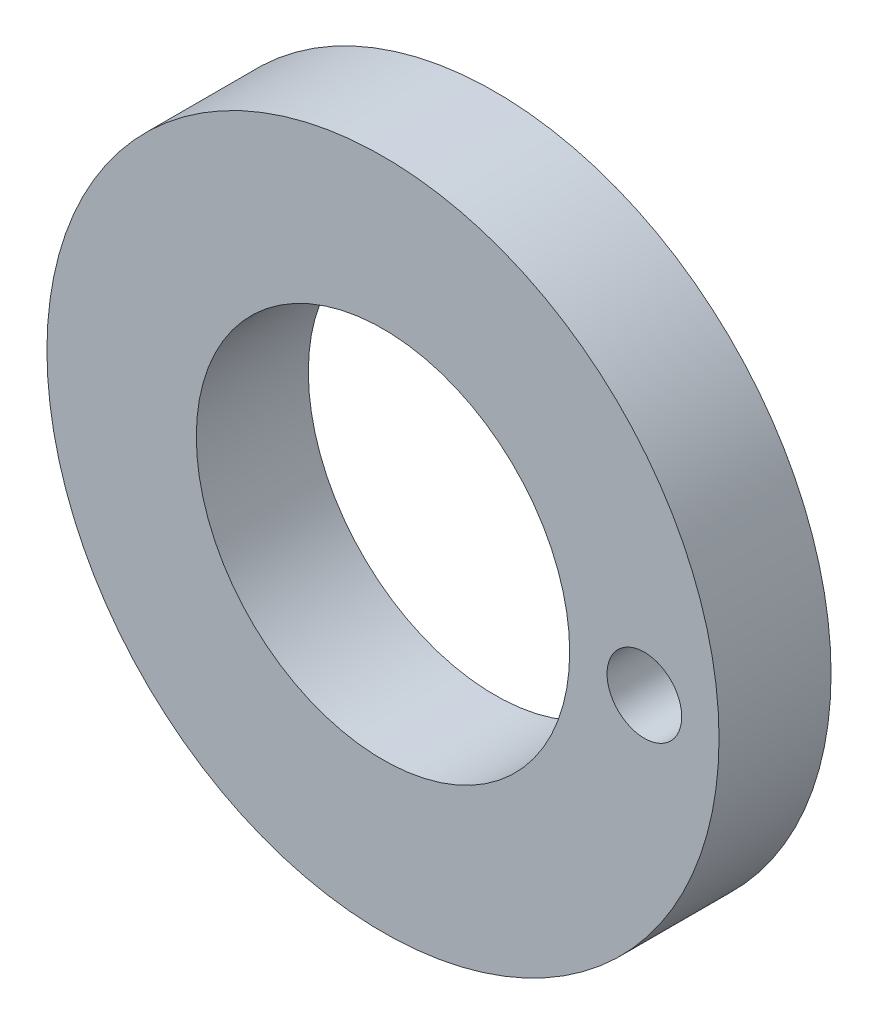
SolidWorks part; units mm, degrees
ref_plane "Front Plane" through (0, 0, 0) normal (0, 0, 1) x (1, 0, 0)
ref_plane "Top Plane" through (0, 0, 0) normal (0, 1, 0) x (1, 0, 0)
ref_plane "Right Plane" through (0, 0, 0) normal (1, 0, 0) x (0, 0, -1)
sketch "Sketch1" plane through (0, 0, 0) normal (0, 0, 1) x (1, 0, 0)
  circle A0 centre (0, 0) radius 90
  dimension "D1" = 180
extrude "Boss-Extrude1" add sketch "Sketch1" along normal blind 30
sketch "Sketch2" plane through (0, 0, 0) normal (0, 0, 1) x (1, 0, 0)
  circle A0 centre (0, 0) radius 50
  dimension "D1" = 100
extrude "Cut-Extrude1" cut sketch "Sketch2" along normal blind 70
sketch "Sketch3" plane through (0, 0, 30) normal (0, 0, 1) x (1, 0, 0)
  circle A1 centre (70, 0) radius 10
  dimension "D1" = 20
extrude "Cut-Extrude2" cut sketch "Sketch3" against normal blind 70
